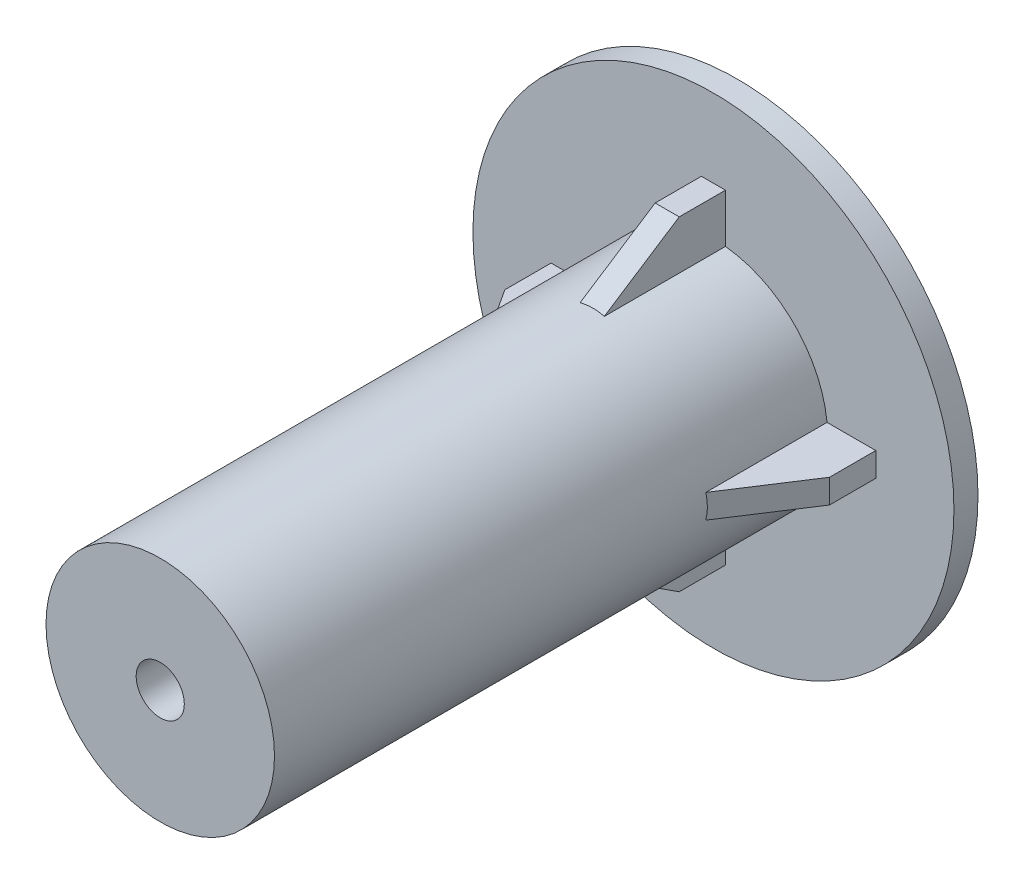
SolidWorks part; units mm, degrees
ref_plane "Front Plane" through (0, 0, 0) normal (0, 0, 1) x (1, 0, 0)
ref_plane "Top Plane" through (0, 0, 0) normal (0, 1, 0) x (1, 0, 0)
ref_plane "Right Plane" through (0, 0, 0) normal (1, 0, 0) x (0, 0, -1)
sketch "Sketch1" plane through (0, 0, 0) normal (0, 0, 1) x (1, 0, 0)
  circle A0 centre (0, 0) radius 47.5
  dimension "D1" = 95
extrude "Boss-Extrude1" add sketch "Sketch1" along normal blind 230
sketch "Sketch2" plane through (0, 0, 230) normal (0, 0, 1) x (1, 0, 0)
  circle A0 centre (0, 0) radius 10
  dimension "D1" = 20
extrude "Cut-Extrude1" cut sketch "Sketch2" against normal blind 20
sketch "Sketch3" plane through (0, 0, 0) normal (0, 0, -1) x (-1, 0, 0)
  circle A0 centre (0, 0) radius 100
  dimension "D1" = 200
extrude "Boss-Extrude2" add sketch "Sketch3" along normal blind 10
sketch "Sketch4" plane through (0, 0, 0) normal (0, 1, 0) x (1, 0, 0)
  line L0 (-47.5, -50) -> (-80, 0)
  line L1 (-47.5, 0) -> (-47.5, -230) construction
  line L2 (-100, 0) -> (100, 0) construction
  dimension "D1" = 50
  dimension "D2" = 80
rib "Rib1" sketch "Sketch4" sketch "Sketch4" thickness 10 extrusion direction parallel to sketch draft on no parameters "D1"=10
pattern_circular "CirPattern1" count 4 over 360 about axis through (0, 0, 0) along (0, 0, 1) of "Rib1"
sketch "Sketch5" plane through (0, 0, 0) normal (0, 1, 0) x (1, 0, 0)
  line L1 (0, 10) -> (0, -190) construction
  line L2 (100, 10) -> (-100, 10) construction
  text T1 "Z0\r\n" font "Century Gothic" height 20
  dimension "D1" = 200
sketch "Sketch6" plane through (0, 0, -10) normal (0, 0, -1) x (-1, 0, 0)
  line L0 (0, 0) -> (0, 300) construction
  line L2 (0, 0) -> (-300, 0) construction
  text T0 "Y0\r\n" font "Century Gothic" height 20
  text T1 "X0\r\n" font "Century Gothic" height 20
  dimension "D1" = 300
sketch "Sketch7" plane through (0, 0, 0) normal (0, 0, 1) x (1, 0, 0)
  line L1 (-67.5, 67.5) -> (67.5, 67.5)
  line L2 (-67.5, 67.5) -> (-67.5, -67.5)
  line L3 (-67.5, -67.5) -> (67.5, -67.5)
  line L4 (67.5, 67.5) -> (67.5, -67.5)
  line L5 (-67.5, 67.5) -> (67.5, -67.5) construction
  line L6 (-67.5, -67.5) -> (67.5, 67.5) construction
  point P0 (0, 0)
  dimension "D1" = 135
extrude "Cut-Extrude2" cut sketch "Sketch7" along normal blind 73 flip side to cut
